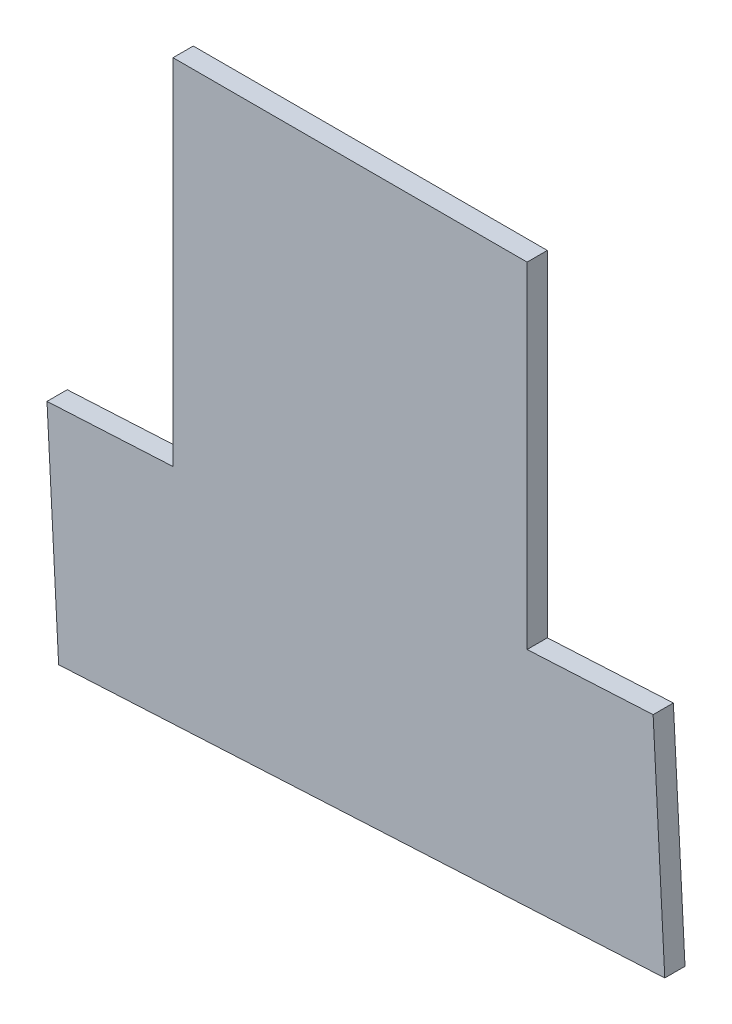
SolidWorks part; units mm, degrees
material "Thornel Mat VMA"
ref_plane "前视基准面" through (0, 0, 0) normal (0, 0, 1) x (1, 0, 0)
ref_plane "上视基准面" through (0, 0, 0) normal (0, 1, 0) x (1, 0, 0)
ref_plane "右视基准面" through (0, 0, 0) normal (1, 0, 0) x (0, 0, -1)
sketch "草图1" plane through (0, 0, 0) normal (0, 0, 1) x (1, 0, 0)
  line L0 (0, 1.8343) -> (-35, 0) construction
  line L2 (0, 1.8343) -> (0, 35)
  line L3 (0, 35) -> (-35, 35)
  line L4 (-35, 0) -> (-35, 35)
  line L5 (-46.3075, -22.6228) -> (13.6103, -19.4826)
  line L6 (13.6103, -19.4826) -> (12.4589, 2.4872)
  line L7 (12.4589, 2.4872) -> (0, 1.8343)
  line L8 (0, 1.8343) -> (-35, 0) construction
  line L9 (-35, 0) -> (104.7856, 0) construction
  line L10 (0, 0) -> (0, 1.8343) construction
  line L12 (-46.3075, -22.6228) -> (-47.4589, -0.6529)
  line L13 (-47.4589, -0.6529) -> (-35, 0)
  point P3 (0, 0)
  point P5 (-48.2875, 0)
  point P6 (-0.5304, 1.8065)
  point P13 (24.7582, 4)
  point P15 (0, 0)
  point P16 (0, 0)
  point P18 (-32.6456, -0.4447)
  point P19 (-41.947, 0)
  point P20 (-35, 0)
  point P21 (-35, 0.4799)
  dimension "D1" = 35
  dimension "D2" = 35
  dimension "D3" = 22
  dimension "D6" = 3
  dimension "D8" = 60
  dimension "D9" = 22
extrude "凸台-拉伸1" add sketch "草图1" along normal blind 2
